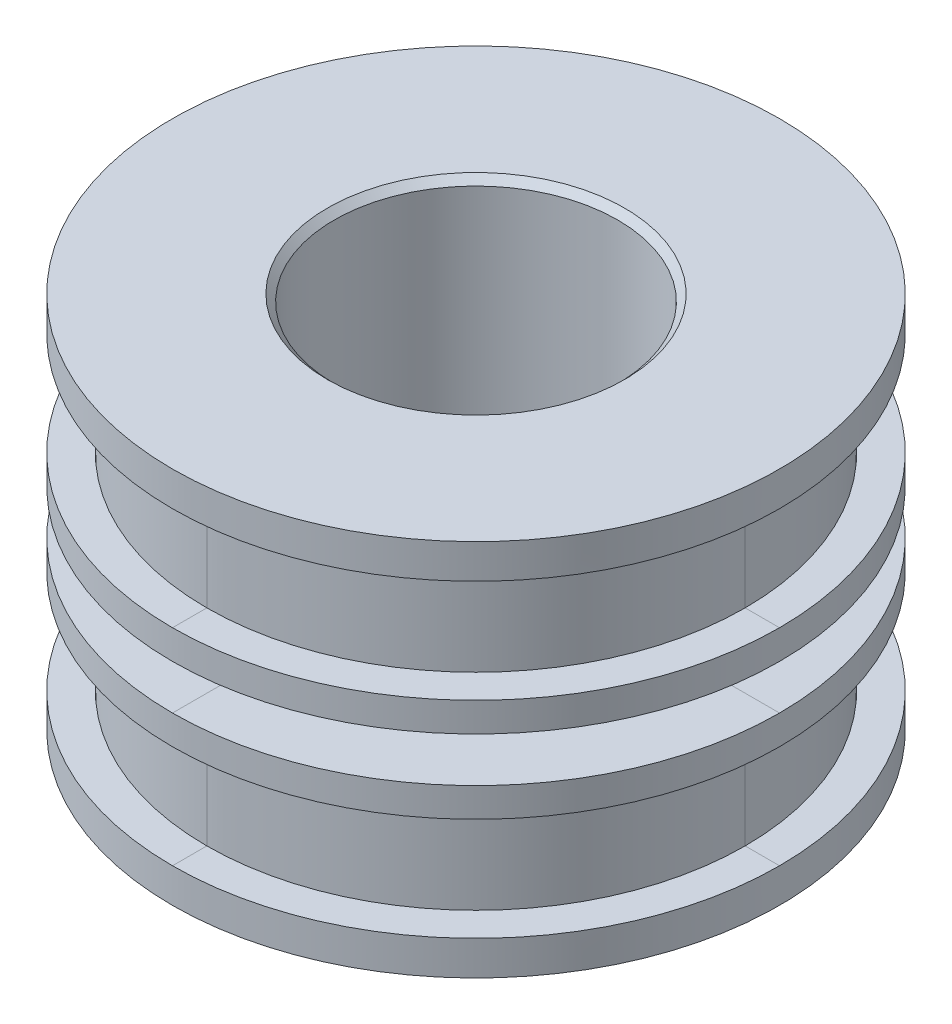
SolidWorks part; units mm, degrees
other "Markup1"
sketch "Sketch2" plane through (65.3273, 15, 65.3273) normal (0.5774, 0.5773, 0.5774) x (0.7071, 0, -0.7071)
ref_plane "Front Plane" through (0, 0, 0) normal (0, 0, 1) x (1, 0, 0)
ref_plane "Top Plane" through (0, 0, 0) normal (0, 1, 0) x (1, 0, 0)
ref_plane "Right Plane" through (0, 0, 0) normal (1, 0, 0) x (0, 0, -1)
sketch "Sketch1" plane through (0, 0, 0) normal (0, 1, 0) x (1, 0, 0)
  circle A0 centre (0, 0) radius 44.175
  dimension "D1" = 88.35
extrude "Boss-Extrude1" add sketch "Sketch1" along normal mid plane 55
sketch "Sketch3" plane through (0, 0, 0) normal (0, 0, 1) x (1, 0, 0)
  line L0 (44.175, -27.5) -> (44.175, 27.5) construction
  line L1 (33.175, -3.25) -> (44.175, -3.25)
  line L2 (33.175, -3.25) -> (33.175, 3.25)
  line L3 (33.175, 3.25) -> (44.175, 3.25)
  line L4 (44.175, -3.25) -> (44.175, 3.25)
  line L5 (33.175, -3.25) -> (44.175, 3.25) construction
  line L6 (33.175, 3.25) -> (44.175, -3.25) construction
  line L7 (-44.175, 0) -> (44.175, 0) construction
  line L8 (-44.175, 27.5) -> (-44.175, -27.5) construction
  point P0 (38.675, 0)
  point P7 (38.675, 0)
  dimension "D1" = 6.5
  dimension "D2" = 11
  dimension "D3" = 5.5
sweep "Cut-Sweep1" cut profiles "Sketch3" path edge at (0, 27.5, 44.175)
sketch "Sketch4" plane through (0, 0, 0) normal (0, 0, 1) x (1, 0, 0)
  line L0 (44.175, 3.25) -> (44.175, 27.5) construction
  line L1 (39.175, 7.5) -> (44.175, 7.5)
  line L2 (39.175, 7.5) -> (39.175, 22.5)
  line L3 (39.175, 22.5) -> (44.175, 22.5)
  line L4 (44.175, 7.5) -> (44.175, 22.5)
  line L5 (39.175, 7.5) -> (44.175, 22.5) construction
  line L6 (39.175, 22.5) -> (44.175, 7.5) construction
  line L7 (44.175, 27.5) -> (-44.175, 27.5) construction
  point P0 (41.675, 15)
  point P9 (39.175, 15)
  dimension "D1" = 5
  dimension "D2" = 15
  dimension "D3" = 5
sweep "Cut-Sweep2" cut profiles "Sketch4" path edge at (0, 27.5, 44.175)
mirror "Mirror1" about plane through (0, 0, 0) normal (0, 1, 0) of "Cut-Sweep2"
sketch "Sketch9" plane through (0, 27.5, 0) normal (0, 1, 0) x (1, 0, 0)
  circle A0 centre (0, 0) radius 20.625
  dimension "D1" = 41.25
extrude "Cut-Extrude2" cut sketch "Sketch9" against normal through all
chamfer "Chamfer1" distance 1 angle 45 1 edges at (0, 27.5, 20.625)
sketch "Sketch10" plane through (0, -27.5, 0) normal (0, -1, 0) x (1, 0, 0)
  circle A0 centre (0, 0) radius 24.5
  dimension "D1" = 49
extrude "Cut-Extrude3" cut sketch "Sketch10" against normal blind 15
chamfer "Chamfer2" distance 1 angle 45 1 edges at (0, -27.5, -24.5)
